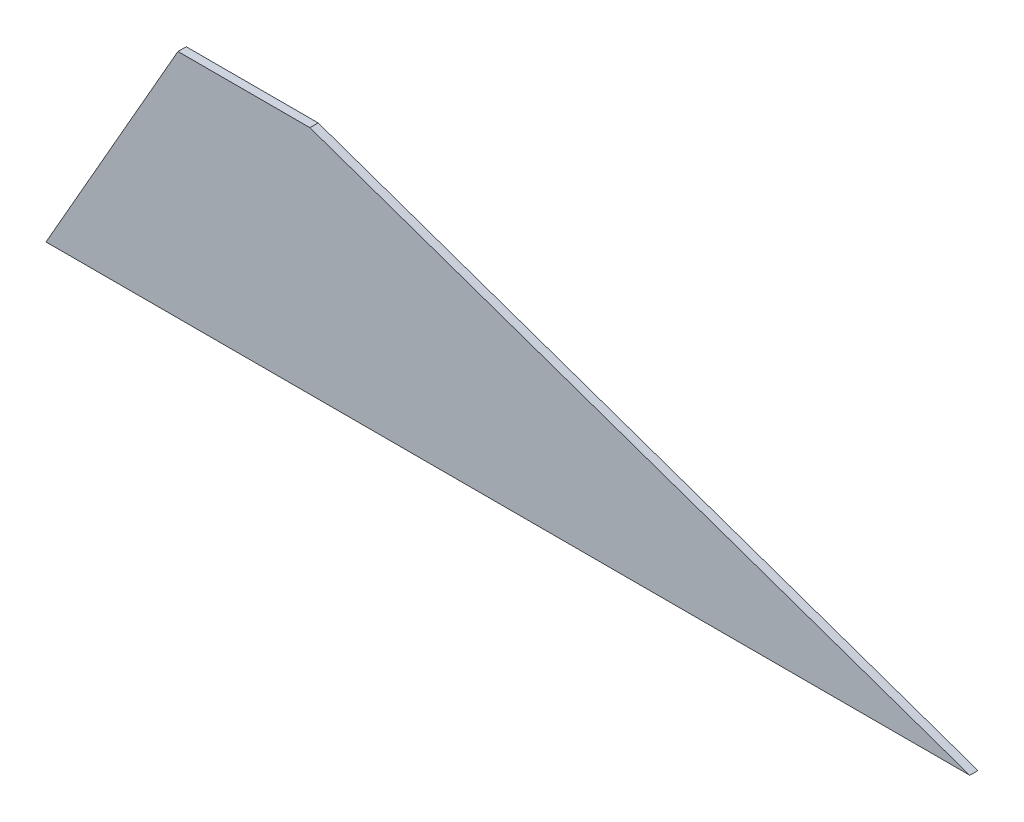
SolidWorks part; units mm, degrees
ref_plane "Front Plane" through (0, 0, 0) normal (0, 0, 1) x (1, 0, 0)
ref_plane "Top Plane" through (0, 0, 0) normal (0, 1, 0) x (1, 0, 0)
ref_plane "Right Plane" through (0, 0, 0) normal (1, 0, 0) x (0, 0, -1)
sketch "Sketch1" plane through (0, 0, 0) normal (0, 0, 1) x (1, 0, 0)
  line L0 (0, 0) -> (-355.6, 0)
  line L1 (-355.6, 0) -> (-304.8, 88.9)
  line L2 (-304.8, 88.9) -> (-254, 88.9)
  line L3 (-254, 88.9) -> (0, 0)
  dimension "D1" = 355.6
  dimension "D2" = 50.8
  dimension "D3" = 50.8
  dimension "D4" = 88.9
extrude "Boss-Extrude1" add sketch "Sketch1" along normal blind 3.175
